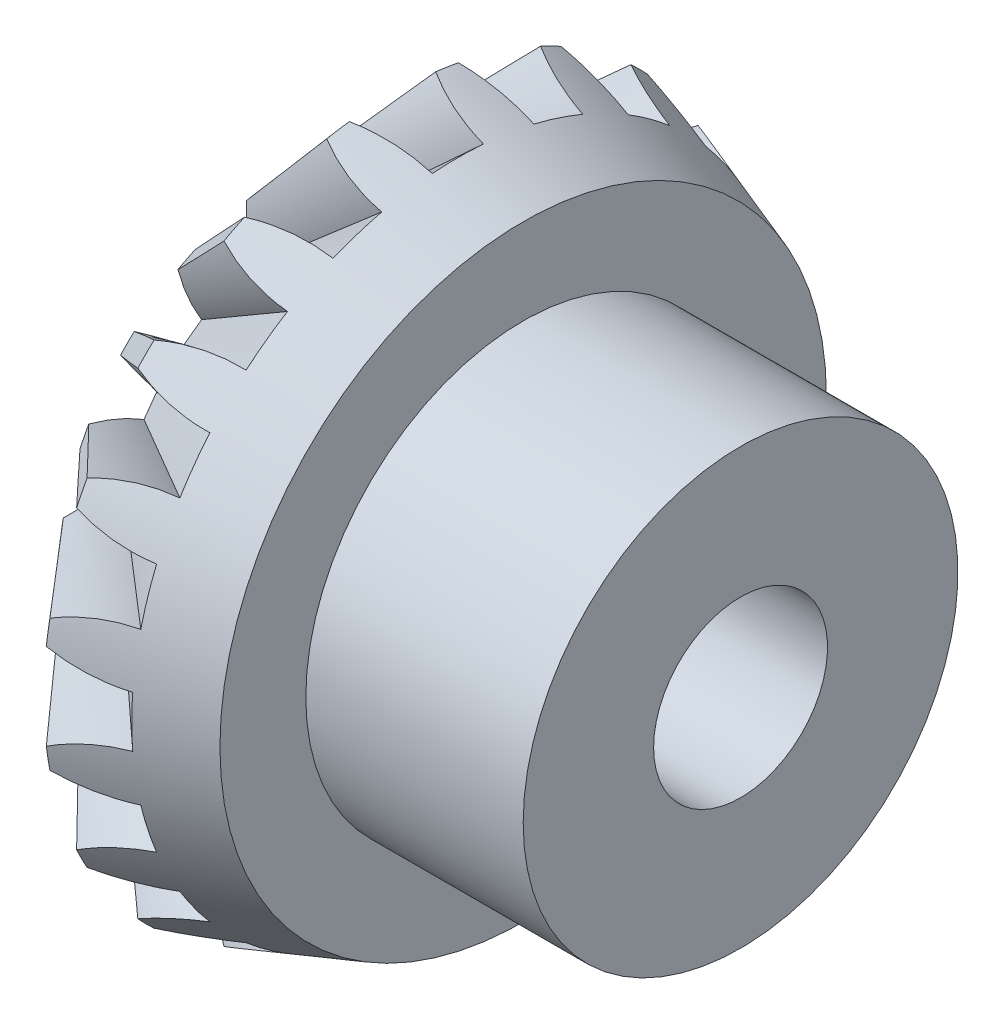
SolidWorks part; units mm, degrees
ref_plane "Front" through (0, 0, 0) normal (0, 0, 1) x (1, 0, 0)
ref_plane "Top" through (0, 0, 0) normal (0, 1, 0) x (1, 0, 0)
ref_plane "Right" through (0, 0, 0) normal (1, 0, 0) x (0, 0, -1)
sketch "Sketch1" plane through (0, 0, 0) normal (0, 0, 1) x (1, 0, 0)
  line L0 (0, 0) -> (20.6, 0) construction
  line L1 (0, 4) -> (20.6, 4)
  line L2 (20.6, 4) -> (20.6, 10)
  line L3 (20.6, 10) -> (10.6, 10)
  line L4 (10.6, 10) -> (10.6, 13.95)
  line L5 (10.6, 13.95) -> (4.5912, 16.05)
  line L6 (4.5912, 16.05) -> (0, 10.766)
  line L7 (0, 10.766) -> (0, 4)
  line L8 (7.5956, 15) -> (0, 6.2582) construction
  dimension "D1" = 49.013
  dimension "Overall Length" = 20.6
  dimension "OD" = 32.1
  dimension "For Shaft" = 8
  dimension "Face Width" = 7
  dimension "Hub Dia" = 20
  dimension "Hub Width" = 10
  dimension "PD" = 30
revolve "Revolve1" add sketch "Sketch1" angle 360 about L0
sketch "Sketch2" plane through (0, 0, 0) normal (-1, 0, 0) x (0, 0, 1)
  circle A0 centre (0, 0) radius 15
  dimension "Pitch Dia" = 30
sketch "Sketch3" plane through (0, 0, 0) normal (-1, 0, 0) x (0, 0, 1)
  line L0 (-10, 0) -> (10, 0) construction
  point P2 (0, 0)
  dimension "teeth" = 20
sketch "Sketch5" plane through (0, 0, 0) normal (-1, 0, 0) x (0, 0, 1)
  line L0 (0, 0) -> (0, 16.05) construction
  line L1 (0, 0) -> (1.2593, 16.0005) construction
  line L2 (0, 0) -> (-1.2593, 16.0005) construction
  line L4 (-10, 0) -> (10, 0) construction
  line L5 (-0.6296, 8.0003) -> (0.6296, 8.0003)
  line L6 (0, 0) -> (-4.9597, 15.2645) construction
  line L7 (0, 0) -> (4.9597, 15.2645) construction
  circle A0 centre (0, 0) radius 16.05 construction
  arc A1 (-0.6296, 8.0003) -> (-4.9597, 15.2645) centre (-10.1441, 7.2515) ccw
  arc A2 (0.6296, 8.0003) -> (4.9597, 15.2645) centre (10.1441, 7.2515) cw
  arc A3 (-4.9597, 15.2645) -> (4.9597, 15.2645) centre (0, 0) cw
  point P10 (0, 0)
  dimension "D1" = 9
  dimension "D2" = 36
ref_plane "Plane1" through (7.5956, 0, 0) normal (1, 0, 0) x (0, 0, -1)
sketch "Sketch6" plane through (7.5956, 0, 0) normal (1, 0, 0) x (0, 0, -1)
  line L0 (0, 0) -> (0, 24.075) construction
  line L1 (0, 0) -> (1.2593, 16.0005) construction
  line L2 (0, 0) -> (-1.2593, 16.0005) construction
  line L3 (0, 0) -> (7.8224, 24.075) construction
  line L4 (0, 0) -> (-7.8224, 24.075) construction
  line L5 (7.8224, 24.075) -> (-7.8224, 24.075) construction
  line L6 (0, 16.05) -> (0, 0) construction
  line L7 (-7.8224, 24.075) -> (7.8224, 24.075)
  circle A0 centre (0, 0) radius 16.05 construction
  arc A1 (-1.1769, 14.9538) -> (-7.8224, 24.075) centre (-11.9197, 14.1083) ccw
  arc A2 (1.1769, 14.9538) -> (7.8224, 24.075) centre (11.9197, 14.1083) cw
  circle A3 centre (0, 0) radius 15 construction
  arc A4 (1.1769, 14.9538) -> (-1.1769, 14.9538) centre (0, 0) ccw
  dimension "D1" = 9
  dimension "D2" = 36
  dimension "D3" = 24.075
  dimension "D4" = 16.05
loft "Cut-Loft1" cut profiles "Sketch6", "Sketch5"
pattern_circular "CirPattern1" count 20 over 360 about axis through (0, 0, 0) along (-1, 0, 0) of "Cut-Loft1"
sketch "Sketch7" plane through (0, 0, 0) normal (-1, 0, 0) x (0, 0, 1)
  circle A0 centre (0, 0) radius 15
sketch "Sketch8" plane through (0, 0, 0) normal (0, 1, 0) x (1, 0, 0)
  line L0 (-9.4, 30) -> (-9.4, 9.4) construction
  line L2 (20.6, -10) -> (20.6, 10) construction
  line B0 (-20.094, 9.4) -> (-25.3266, 13.9912) construction
  line B1 (-25.3266, 13.9912) -> (-23.35, 20) construction
  line B2 (-23.35, 20) -> (-19.4, 20) construction
  line B3 (-19.4, 20) -> (-19.4, 30) construction
  line B4 (-19.4, 30) -> (0.6, 30) construction
  line B5 (0.6, 30) -> (0.6, 20) construction
  line B6 (0.6, 20) -> (4.55, 20) construction
  line B7 (4.55, 20) -> (6.5266, 13.9912) construction
  line B8 (6.5266, 13.9912) -> (1.294, 9.4) construction
  line B9 (1.294, 9.4) -> (-20.094, 9.4) construction
  dimension "D1" = 30
  dimension "D2" = 30
sketch_block_instance "Block2-1"
sketch_block "Block2"
equation "\"D1@Sketch5\"=(360deg/20)/2"
equation "\"D2@Sketch5\"=(360deg/20)/.5"
equation "\"D1@Sketch6\"=(360deg/\"teeth@Sketch5\")/2"
equation "\"D2@Sketch6\"=(360deg/\"teeth@Sketch5\")/.5"
equation "\"D3@Sketch6\"=\"D4@Sketch6\"*1.5"
